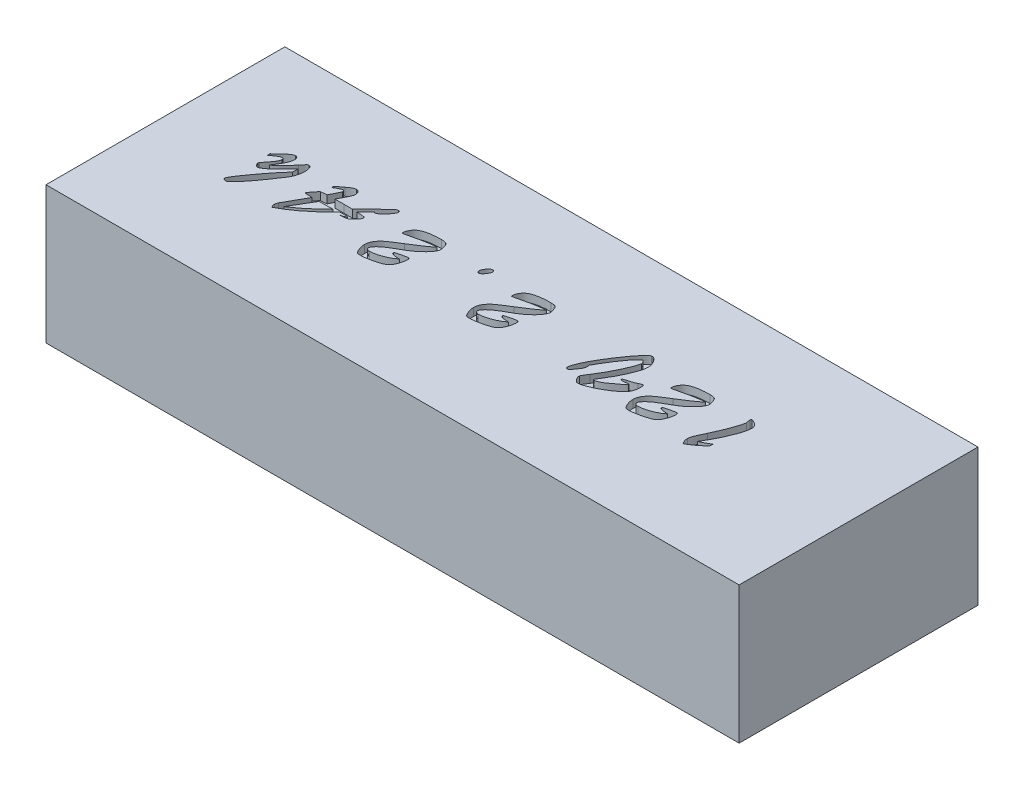
SolidWorks part; units mm, degrees
ref_plane "前视基准面" through (0, 0, 0) normal (0, 0, 1) x (1, 0, 0)
ref_plane "上视基准面" through (0, 0, 0) normal (0, 1, 0) x (1, 0, 0)
ref_plane "右视基准面" through (0, 0, 0) normal (1, 0, 0) x (0, 0, -1)
sketch "草图15" plane through (0, 0, 0) normal (0, 0, 1) x (1, 0, 0)
  line L0 (-133.5095, 0) -> (117.414, 0) construction
  line L1 (0, -131.4759) -> (0, 109.2718) construction
  line L3 (-88.5, 17.5) -> (88.5, 17.5)
  line L4 (-88.5, 17.5) -> (-88.5, -17.5)
  line L5 (-88.5, -17.5) -> (88.5, -17.5)
  line L6 (88.5, 17.5) -> (88.5, -17.5)
  dimension "D1" = 35
  dimension "D2" = 177
extrude "拉伸1" add sketch "草图15" along normal blind 61
sketch "草图17" plane through (0, 17.5, 0) normal (0, 1, 0) x (-1, 0, 0)
  text T0 "12V 2.2Ah" font "华文行楷" height 15
extrude "切除-拉伸1" cut sketch "草图17" against normal blind 2
